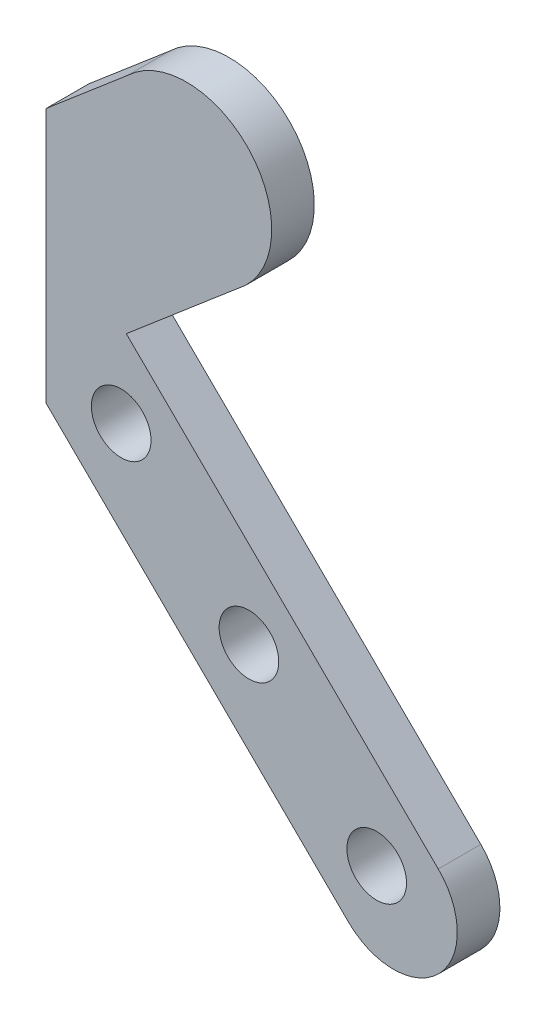
SolidWorks part; units mm, degrees
ref_plane "Front Plane" through (0, 0, 0) normal (0, 0, 1) x (1, 0, 0)
ref_plane "Top Plane" through (0, 0, 0) normal (0, 1, 0) x (1, 0, 0)
ref_plane "Right Plane" through (0, 0, 0) normal (1, 0, 0) x (0, 0, -1)
sketch "Sketch1" plane through (0, 0, 0) normal (0, 0, 1) x (1, 0, 0)
  line L14 (5.5498, -33.3031) -> (5.5498, -93.3031)
  line L15 (5.5498, -93.3031) -> (76.5498, -163.3031)
  line L19 (5.5498, -33.3031) -> (24.5864, -17.098)
  line L21 (97.612, -141.94) -> (24.3559, -69.7157)
  line L22 (24.3559, -69.7157) -> (52.4205, -45.8254)
  line L23 (5.5498, -63.3031) -> (65.5544, -62.8776) construction
  arc A0 (24.5864, -17.098) -> (52.4205, -45.8254) centre (38.5035, -31.4617) cw
  arc A1 (76.5498, -163.3031) -> (97.612, -141.94) centre (87.0809, -152.6216) ccw
  point P5 (0, 0)
  point P10 (0, 0)
  dimension "D9" = 15
  dimension "D10" = 20
  dimension "D1" = 25
  dimension "D2" = 40
  dimension "D3" = 71
  dimension "D4" = 30
  dimension "D5" = 60
  dimension "D6" = 70
  dimension "D7" = 45
  dimension "D8" = 40
extrude "Boss-Extrude1" add sketch "Sketch1" along normal blind 10
sketch "Sketch2" plane through (0, 0, 10) normal (0, 0, 1) x (1, 0, 0)
  line L0 (97.7624, -163.1527) -> (5.5498, -70.94) construction
  line L1 (5.5498, -33.3031) -> (5.5498, -93.3031) construction
  arc A0 (76.5498, -163.3031) -> (97.612, -141.94) centre (87.0809, -152.6216) ccw construction
  circle A1 centre (23.1519, -88.5421) radius 7
  circle A2 centre (53.1519, -118.5421) radius 7
  circle A3 centre (83.1519, -148.5421) radius 7
  point P15 (25.1427, -92.8838)
  dimension "D1" = 14
  dimension "D2" = 30
  dimension "D3" = 30
  dimension "D4" = 30
extrude "Cut-Extrude1" cut sketch "Sketch2" against normal through all
